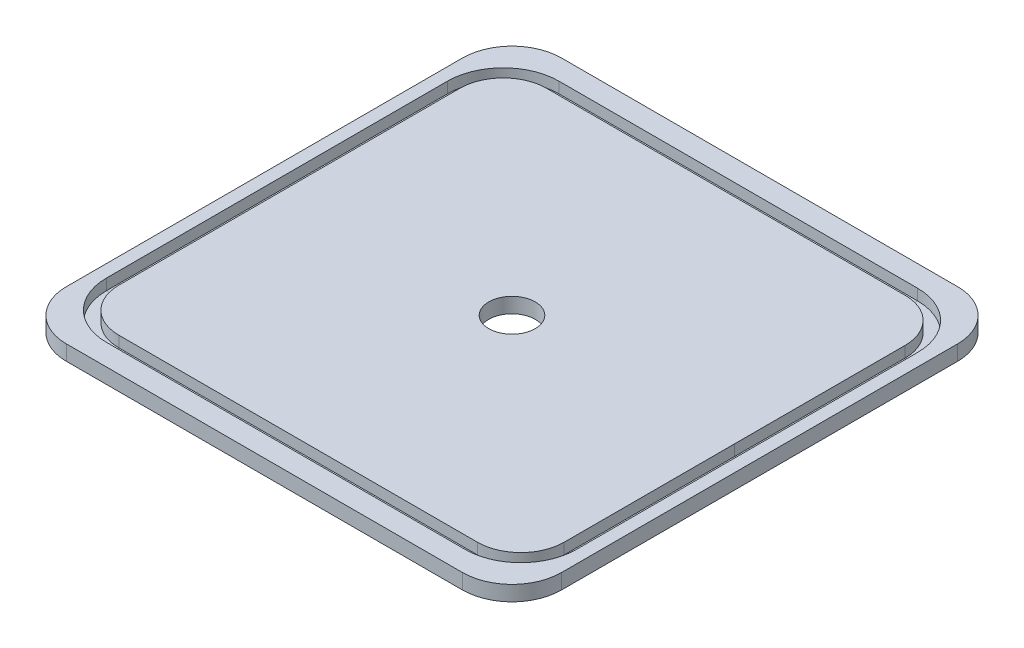
SolidWorks part; units mm, degrees
ref_plane "Front Plane" through (0, 0, 0) normal (0, 0, 1) x (1, 0, 0)
ref_plane "Top Plane" through (0, 0, 0) normal (0, 1, 0) x (1, 0, 0)
ref_plane "Right Plane" through (0, 0, 0) normal (1, 0, 0) x (0, 0, -1)
sketch "Sketch1" plane through (0, 0, 0) normal (0, 1, 0) x (1, 0, 0)
  line L0 (0, 63.5) -> (0, -63.5) construction
  line L12 (-63.5, 50.8) -> (-63.5, -50.8)
  line L13 (-50.8, -63.5) -> (50.8, -63.5)
  line L14 (63.5, -50.8) -> (63.5, 50.8)
  line L15 (50.8, 63.5) -> (-50.8, 63.5)
  arc A0 (50.8, -63.5) -> (63.5, -50.8) centre (50.8, -50.8) ccw
  arc A1 (63.5, 50.8) -> (50.8, 63.5) centre (50.8, 50.8) ccw
  arc A2 (-63.5, -50.8) -> (-50.8, -63.5) centre (-50.8, -50.8) ccw
  arc A3 (-63.5, 50.8) -> (-50.8, 63.5) centre (-50.8, 50.8) cw
  point P11 (-63.5, 0)
  point P15 (0, 63.5)
  point P16 (0, 0)
  dimension "D3" = 12.7
  dimension "D1" = 127
  dimension "D2" = 127
extrude "main body" add sketch "Sketch1" along normal mid plane 3.8837
sketch "Sketch29" plane through (0, 1.9418, 0) normal (0, 1, 0) x (1, 0, 0)
  line L0 (0, 63.5) -> (0, -63.5)
  line L4 (63.5, -50.8) -> (63.5, 50.8)
  line L5 (50.8, 63.5) -> (-50.8, 63.5)
  line L6 (-63.5, 50.8) -> (-63.5, -50.8)
  line L7 (-50.8, -63.5) -> (50.8, -63.5)
  line L8 (63.5, -50.8) -> (63.5, 50.8)
  line L9 (50.8, 63.5) -> (-50.8, 63.5)
  line L10 (-63.5, 50.8) -> (-63.5, -50.8)
  line L11 (-50.8, -63.5) -> (50.8, -63.5)
  circle A1 centre (0, 0) radius 5.9531
  arc A4 (50.8, -63.5) -> (63.5, -50.8) centre (50.8, -50.8) ccw
  arc A5 (63.5, 50.8) -> (50.8, 63.5) centre (50.8, 50.8) ccw
  arc A6 (-50.8, 63.5) -> (-63.5, 50.8) centre (-50.8, 50.8) ccw
  arc A7 (-63.5, -50.8) -> (-50.8, -63.5) centre (-50.8, -50.8) ccw
  arc A8 (50.8, -63.5) -> (63.5, -50.8) centre (50.8, -50.8) ccw
  arc A9 (63.5, 50.8) -> (50.8, 63.5) centre (50.8, 50.8) ccw
  arc A10 (-50.8, 63.5) -> (-63.5, 50.8) centre (-50.8, 50.8) ccw
  arc A11 (-63.5, -50.8) -> (-50.8, -63.5) centre (-50.8, -50.8) ccw
  dimension "D1" = 0
extrude "PneumaticMount" cut sketch "Sketch29" against normal up to surface (3.8837 mm away) up to face at (0, -1.9418, 0)
sketch "ORingInsertPath" plane through (0, 1.9418, 0) normal (0, 1, 0) x (1, 0, 0)
  line L4 (-45.9922, -56.4388) -> (45.9922, -56.4388)
  line L5 (58.6922, -43.7388) -> (58.6922, 43.7388)
  line L6 (45.9922, 56.4388) -> (-45.9922, 56.4388)
  line L7 (-58.6922, 43.7388) -> (-58.6922, -43.7388)
  line L8 (-45.9922, -56.4388) -> (45.9922, -56.4388)
  line L9 (58.6922, -43.7388) -> (58.6922, 43.7388)
  line L10 (45.9922, 56.4388) -> (-45.9922, 56.4388)
  line L11 (-58.6922, 43.7388) -> (-58.6922, -43.7388)
  line L28 (-58.6922, 0) -> (58.6922, 0) construction
  arc A4 (-58.6922, -43.7388) -> (-45.9922, -56.4388) centre (-45.9922, -43.7388) ccw
  arc A5 (45.9922, -56.4388) -> (58.6922, -43.7388) centre (45.9922, -43.7388) ccw
  arc A6 (58.6922, 43.7388) -> (45.9922, 56.4388) centre (45.9922, 43.7388) ccw
  arc A7 (-45.9922, 56.4388) -> (-58.6922, 43.7388) centre (-45.9922, 43.7388) ccw
  arc A8 (-58.6922, -43.7388) -> (-45.9922, -56.4388) centre (-45.9922, -43.7388) ccw
  arc A9 (45.9922, -56.4388) -> (58.6922, -43.7388) centre (45.9922, -43.7388) ccw
  arc A10 (58.6922, 43.7388) -> (45.9922, 56.4388) centre (45.9922, 43.7388) ccw
  arc A11 (-45.9922, 56.4388) -> (-58.6922, 43.7388) centre (-45.9922, 43.7388) ccw
  dimension "D1" = 0
sketch "ORingInsertProfile" plane through (0, 0, 0) normal (0, 0, 1) x (1, 0, 0)
  line L1 (60.281, 1.9418) -> (57.1034, 1.9418)
  line L2 (60.281, 1.9418) -> (60.281, -0.8826)
  line L3 (60.281, -0.8826) -> (57.1034, -0.8827)
  line L4 (57.1034, 1.9418) -> (57.1034, -0.8827)
  line L5 (57.1034, 1.9418) -> (60.281, 1.9418) construction
  line L6 (5.9531, 1.9418) -> (-5.9531, 1.9418) construction
  point P8 (58.6922, 1.9418)
  dimension "D1" = 3.1775
  dimension "D2" = 2.8245
sweep "O-RingInsert" cut profiles "ORingInsertProfile" path "ORingInsertPath"
equation "\"BodyLength\" = \"BaseLength@BladderAssembly.Assembly\""
equation "\"BodyWidth\" = \"BaseWidth@BladderAssembly.Assembly\""
equation "\"D1@main body\" = 1.1 * \"O-Ring_CS@BladderAssembly.Assembly\""
equation "\"HookDepth\"= 0.25"
equation "\"O-RingDiameter\"= 7.512in'McMaster 9396K255"
equation "\"BodyHeight\"= \"overall_thickness\" - \"window_thickness\" - \"sheet_thickness\""
equation "\"window_thickness\"= 0.0625in"
equation "\"sheet_thickness\"= 0.03125in"
equation "\"overall_thickness\"= 7mm"
equation "\"O-RingDiameter\"= 7.512in 'McMaster 9396K255"
equation "\"D2@Sketch1\"=\"BodyLength\""
equation "\"D1@Sketch1\"=\"BodyWidth\""
equation "\"HookWidth\"= 0.25in"
equation "\"D1@ORingInsertProfile\" = 0.9 * \"O-Ring_CS@BladderAssembly.Assembly\""
equation "\"O-Ring_CutDepth\"= 0.8 * \"O-Ring_CS@BladderAssembly.Assembly\""
equation "\"D2@ORingInsertProfile\"=\"O-Ring_CutDepth\""
